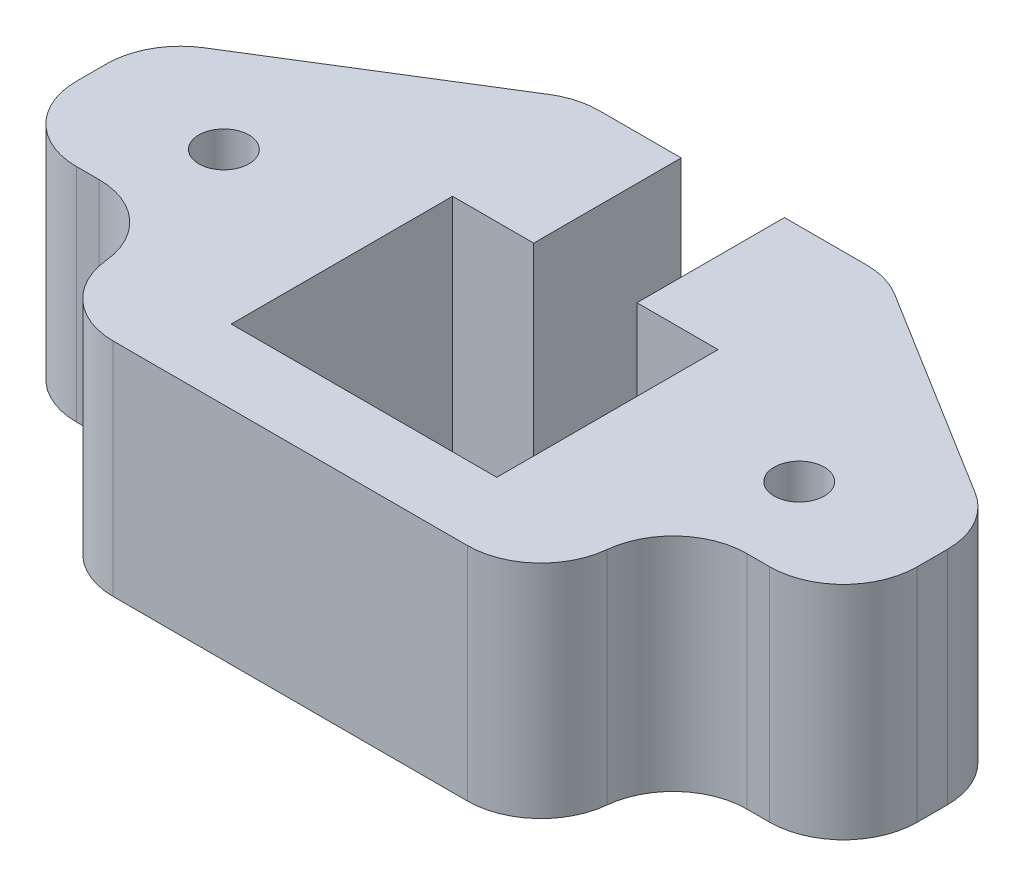
SolidWorks part; units mm, degrees
material "POM 乙缩醛共聚物"
ref_plane "前视基准面" through (0, 0, 0) normal (0, 0, 1) x (1, 0, 0)
ref_plane "上视基准面" through (0, 0, 0) normal (0, 1, 0) x (1, 0, 0)
ref_plane "右视基准面" through (0, 0, 0) normal (1, 0, 0) x (0, 0, -1)
sketch "草图1" plane through (0, 0, 0) normal (0, 1, 0) x (1, 0, 0)
  line L0 (0, 0) -> (0, -21)
  line L1 (11.5, -30) -> (45.5, -30)
  line L2 (57, -21) -> (57, 0)
  line L3 (57, 0) -> (32, 0)
  line L4 (32, 0) -> (32, -10)
  line L6 (25, -10) -> (25, 0)
  line L7 (25, 0) -> (0, 0)
  line L8 (32, -10) -> (37.5, -10)
  line L9 (37.5, -10) -> (37.5, -25)
  line L10 (37.5, -25) -> (19.5, -25)
  line L11 (19.5, -25) -> (19.5, -10)
  line L12 (19.5, -10) -> (25, -10)
  line L13 (0, -21) -> (11.5, -21)
  line L14 (11.5, -21) -> (11.5, -30)
  line L15 (57, -21) -> (45.5, -21)
  line L16 (45.5, -21) -> (45.5, -30)
  circle A0 centre (9, -15) radius 1.7
  circle A1 centre (48, -15) radius 1.7
  dimension "D10" = 3.4
  dimension "D13" = 3.4
  dimension "D14" = 9
  dimension "D15" = 15
  dimension "D2" = 21
  dimension "D3" = 7
  dimension "D4" = 15
  dimension "D5" = 18
  dimension "D6" = 5.5
  dimension "D7" = 25
  dimension "D8" = 10
  dimension "D9" = 10
  dimension "D11" = 9
  dimension "D12" = 15
  dimension "D16" = 6
  dimension "D17" = 8
  dimension "D18" = 8
  dimension "D19" = 25
extrude "凸台-拉伸1" add sketch "草图1" along normal blind 15
sketch "草图2" plane through (0, 15, 0) normal (0, 1, 0) x (1, 0, 0)
  line L0 (18, 0) -> (0, -11.1697)
  line L1 (25, 0) -> (0, 0) construction
  line L2 (0, 0) -> (0, -21) construction
  line L3 (25, -10) -> (25, 0) construction
  line L4 (0, -11.1697) -> (0, 0)
  line L5 (0, 0) -> (18, 0)
  line L6 (28.5, -25) -> (28.5, -18.3435) construction
  line L7 (37.5, -25) -> (19.5, -25) construction
  line L8 (57, 0) -> (39, 0)
  line L9 (57, -11.1697) -> (57, 0)
  line L10 (39, 0) -> (57, -11.1697)
  circle A0 centre (9, -15) radius 1.7 construction
  dimension "D1" = 7
  dimension "D2" = 8
extrude "切除-拉伸1" cut sketch "草图2" against normal blind 19
fillet "圆角2" radius 5 8 edges at (0, 7.5, 11.1697) (57, 7.5, 11.1697) (39, 7.5, 0) (18, 7.5, 0) (57, 7.5, 21) (45.5, 7.5, 30) (11.5, 7.5, 30) (0, 7.5, 21)
fillet "圆角3" radius 5 2 edges at (45.5, 7.5, 21) (11.5, 7.5, 21)
